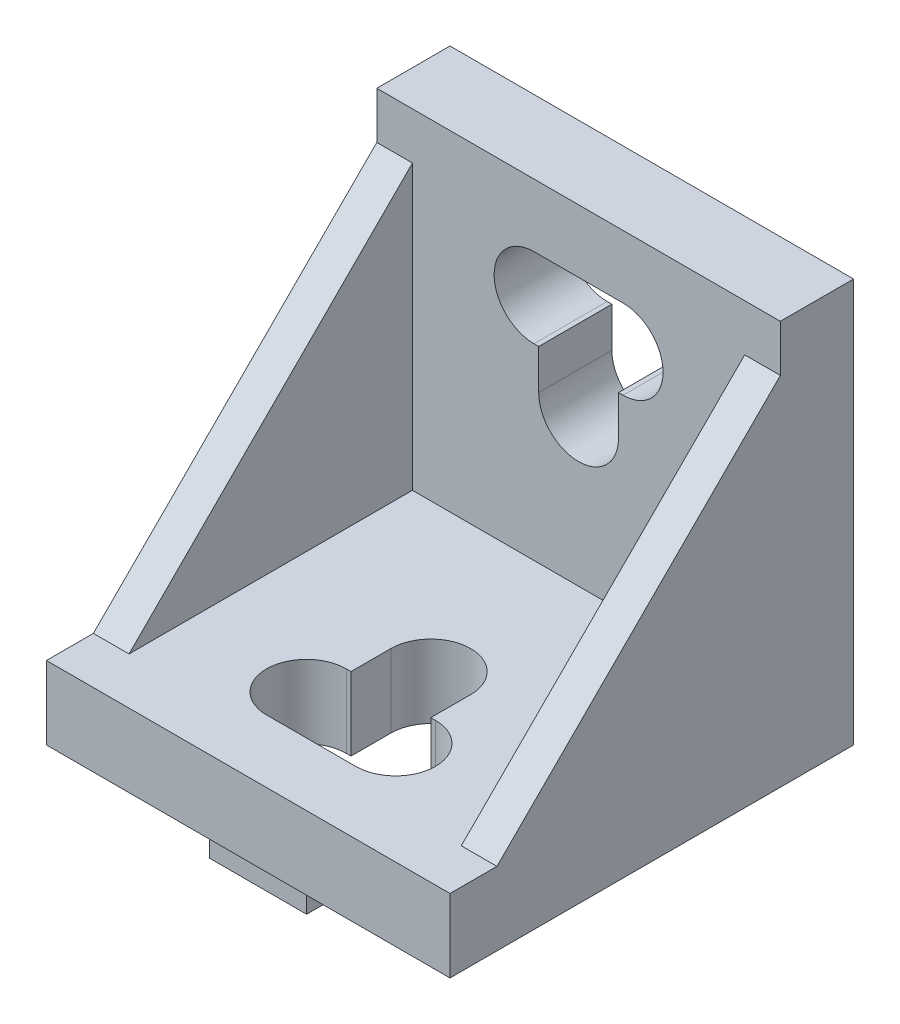
SolidWorks part; units mm, degrees
ref_plane "前视基准面" through (0, 0, 0) normal (0, 0, 1) x (1, 0, 0)
ref_plane "上视基准面" through (0, 0, 0) normal (0, 1, 0) x (1, 0, 0)
ref_plane "右视基准面" through (0, 0, 0) normal (1, 0, 0) x (0, 0, -1)
sketch "草图1" plane through (0, 0, 0) normal (0, 0, 1) x (1, 0, 0)
  line L1 (-21.5, -21.5) -> (21.5, -21.5)
  line L2 (-21.5, -21.5) -> (-21.5, 21.5)
  line L3 (-21.5, 21.5) -> (21.5, 21.5)
  line L4 (21.5, -21.5) -> (21.5, 21.5)
  line L5 (-21.5, -21.5) -> (21.5, 21.5) construction
  line L6 (-21.5, 21.5) -> (21.5, -21.5) construction
  point P0 (0, 0)
  dimension "D1" = 43
  dimension "D2" = 43
extrude "凸台-拉伸1" add sketch "草图1" along normal blind 7.8
sketch "草图3" plane through (0, -21.5, 0) normal (0, -1, 0) x (1, 0, 0)
  line L0 (-21.5, 0) -> (21.5, 0)
  line L1 (-21.5, 0) -> (-21.5, 43)
  line L2 (21.5, 0) -> (21.5, 43)
  line L3 (-21.5, 43) -> (21.5, 43)
  dimension "D1" = 43
extrude "凸台-拉伸2" add sketch "草图3" against normal blind 7.8
sketch "草图4" plane through (-21.5, 0, 0) normal (-1, 0, 0) x (0, 0, 1)
  line L0 (7.8, 16.5) -> (38, -13.7)
  line L1 (7.8, 21.5) -> (7.8, -13.7) construction
  line L2 (43, -13.7) -> (7.8, -13.7) construction
  line L3 (7.8, 16.5) -> (7.8, -13.7)
  line L4 (7.8, -13.7) -> (38, -13.7)
  line L6 (7.8, 21.5) -> (0, 21.5) construction
  dimension "D1" = 5
  dimension "D2" = 5
extrude "凸台-拉伸3" add sketch "草图4" against normal blind 3.8
mirror "镜向1" about plane through (0, 0, 0) normal (1, 0, 0) of "凸台-拉伸3"
sketch "草图5" plane through (0, 0, 7.8) normal (0, 0, 1) x (1, 0, 0)
  line L0 (0, 2.05) -> (0, 10.55) construction
  line L1 (-4.25, 2.05) -> (-4.25, 6.3)
  line L2 (4.25, 2.05) -> (4.25, 6.3)
  line L4 (4.75, 10.55) -> (-4.75, 10.55) construction
  line L5 (4.75, 6.3) -> (4.25, 6.3)
  line L6 (4.75, 14.8) -> (-4.75, 14.8)
  line L7 (-4.25, 6.3) -> (-4.75, 6.3)
  arc A0 (-4.25, 2.05) -> (4.25, 2.05) centre (0, 2.05) ccw
  arc A2 (4.75, 6.3) -> (4.75, 14.8) centre (4.75, 10.55) ccw
  arc A3 (-4.75, 14.8) -> (-4.75, 6.3) centre (-4.75, 10.55) ccw
  point P3 (0, 6.3)
  point P12 (0, 10.55)
  point P17 (0, 14.8)
  dimension "D4" = 4.25
  dimension "D6" = 0
  dimension "D5" = 9.5
extrude "切除-拉伸1" cut sketch "草图5" against normal through all
ref_plane "基准面1" through (0, -10.75, 10.75) normal (0, 0.7071, -0.7071) x (-1, 0, 0)
mirror "镜向2" about plane through (0, -10.75, 10.75) normal (0, 0.7071, -0.7071) of "切除-拉伸1"
sketch "草图6" plane through (0, -21.5, 0) normal (0, -1, 0) x (1, 0, 0)
  line L1 (-5.1825, 41.9583) -> (5.1825, 41.9583)
  line L2 (-5.1825, 41.9583) -> (-5.1825, 39.1583)
  line L3 (-5.1825, 39.1583) -> (5.1825, 39.1583)
  line L4 (5.1825, 41.9583) -> (5.1825, 39.1583)
  line L5 (-5.1825, 41.9583) -> (5.1825, 39.1583) construction
  line L6 (-5.1825, 39.1583) -> (5.1825, 41.9583) construction
  point P0 (0, 40.5583)
  dimension "D1" = 2.8
extrude "凸台-拉伸5" add sketch "草图6" along normal blind 2.8
